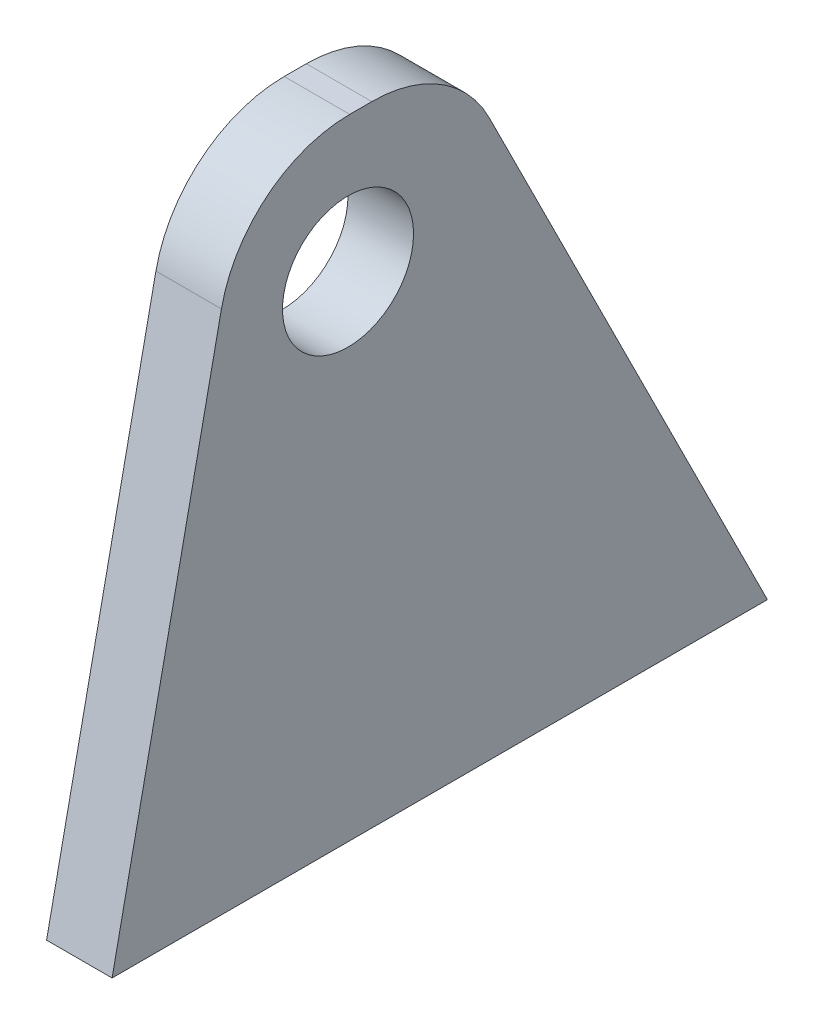
SolidWorks part; units mm, degrees
material "AISI 4340 Steel, normalized"
ref_plane "X-Y Datum" through (0, 0, 0) normal (0, 0, 1) x (1, 0, 0)
ref_plane "X-Z Datum" through (0, 0, 0) normal (0, 1, 0) x (1, 0, 0)
ref_plane "Y-Z Datum" through (0, 0, 0) normal (1, 0, 0) x (0, 0, -1)
sketch "Sketch1" plane through (0, 0, 0) normal (1, 0, 0) x (0, 0, -1)
  line L0 (31.75, 0) -> (16.51, 30.48)
  line L1 (16.51, 30.48) -> (6.35, 30.48)
  line L2 (6.35, 30.48) -> (0, 0)
  line L3 (0, 0) -> (31.75, 0)
  circle A0 centre (11.43, 23.9281) radius 3.175
  dimension "D5" = 23.9281
  dimension "D6" = 6.35
  dimension "D7" = 11.43
  dimension "D1" = 31.75
  dimension "D2" = 15.24
  dimension "D3" = 30.48
  dimension "D4" = 10.16
extrude "Boss-Extrude1" add sketch "Sketch1" along normal blind 3.175
fillet "Fillet2" radius 6.35 2 edges at (1.5875, 30.48, -16.51) (1.5875, 30.48, -6.35)
